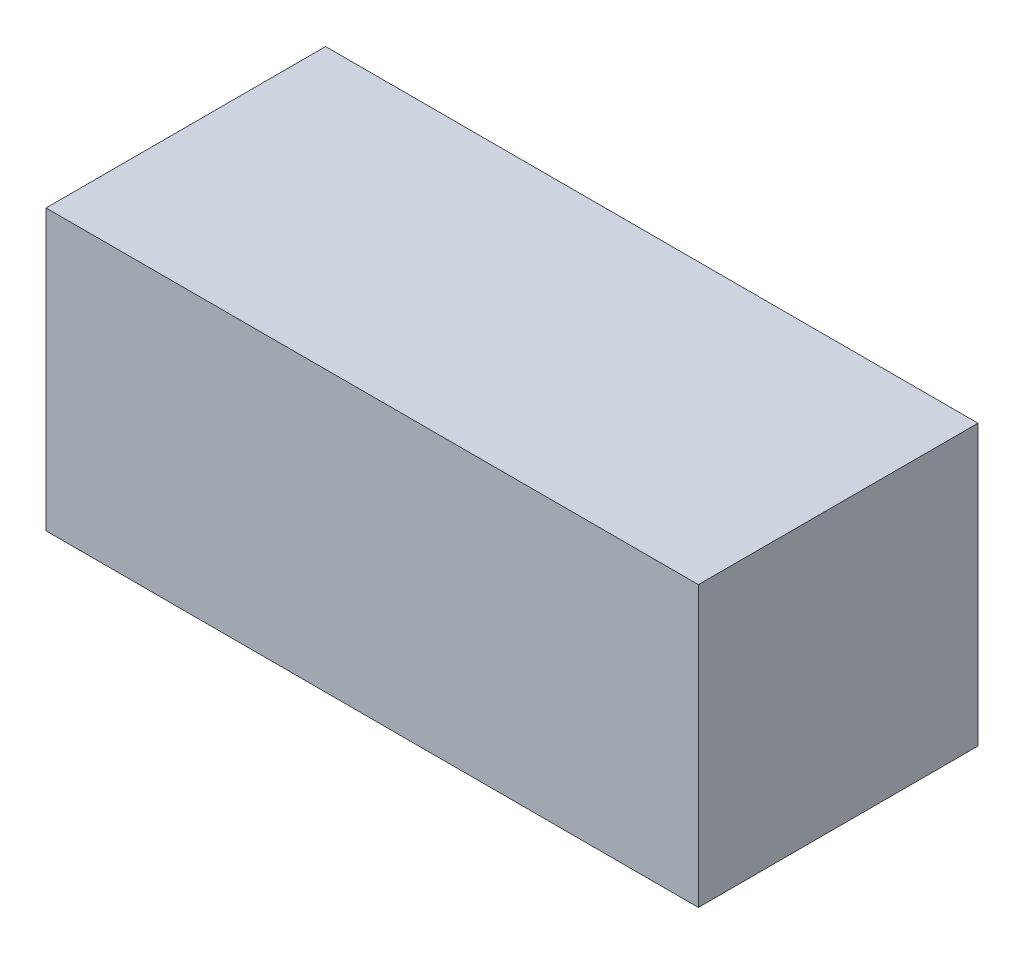
SolidWorks part; units mm, degrees
ref_plane "Front Plane" through (0, 0, 0) normal (0, 0, 1) x (1, 0, 0)
ref_plane "Top Plane" through (0, 0, 0) normal (0, 1, 0) x (1, 0, 0)
ref_plane "Right Plane" through (0, 0, 0) normal (1, 0, 0) x (0, 0, -1)
sketch "Sketch1" plane through (0, 0, 0) normal (1, 0, 0) x (0, 0, -1)
  line L1 (0, 0) -> (38.1, 0)
  line L2 (0, 0) -> (0, 38.1)
  line L3 (0, 38.1) -> (38.1, 38.1)
  line L4 (38.1, 0) -> (38.1, 38.1)
  dimension "D1" = 38.1
  dimension "D2" = 38.1
extrude "Boss-Extrude1" add sketch "Sketch1" along normal blind 88.9
